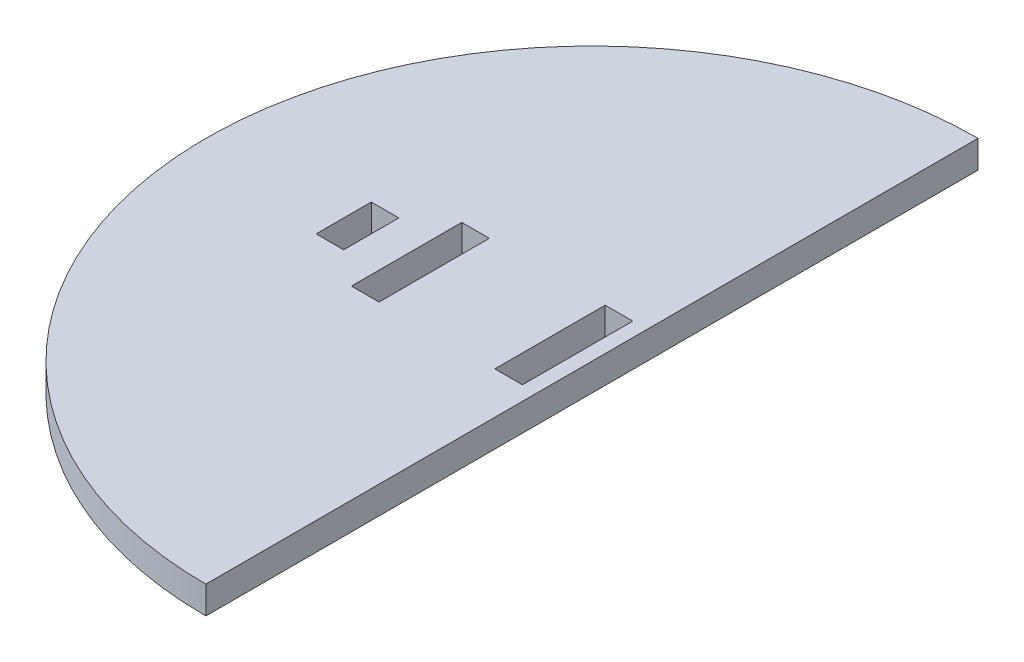
SolidWorks part; units mm, degrees
ref_plane "Front Plane" through (0, 0, 0) normal (0, 0, 1) x (1, 0, 0)
ref_plane "Top Plane" through (0, 0, 0) normal (0, 1, 0) x (1, 0, 0)
ref_plane "Right Plane" through (0, 0, 0) normal (1, 0, 0) x (0, 0, -1)
sketch "Sketch1" plane through (0, 0, 0) normal (0, 1, 0) x (1, 0, 0)
  line L0 (0, 70) -> (0, -70)
  line L2 (-45, -5) -> (-40, -5)
  line L3 (-45, -5) -> (-45, 5)
  line L4 (-45, 5) -> (-40, 5)
  line L5 (-40, -5) -> (-40, 5)
  line L6 (-45, -5) -> (-40, 5) construction
  line L7 (-45, 5) -> (-40, -5) construction
  arc A0 (0, 70) -> (0, -70) centre (0, 0) ccw
  point P4 (-42.5, 0)
  dimension "D1" = 70
  dimension "D5" = 140
  dimension "D2" = 10
  dimension "D3" = 5
  dimension "D4" = 40
extrude "Boss-Extrude1" add sketch "Sketch1" along normal blind 5 contours L0 A0 | L3 L2 L5 L4
sketch "Sketch2" plane through (0, 5, 0) normal (0, 1, 0) x (1, 0, 0)
  line L7 (0, 0) -> (-2.6, 0)
  line L8 (0, 70) -> (0, -70) construction
  line L9 (-2.6, 0) -> (-2.6, 10)
  line L10 (-2.6, 10) -> (-7.6, 10)
  line L11 (-7.6, 10) -> (-7.6, -10)
  line L12 (-7.6, -10) -> (-2.6, -10)
  line L13 (-2.6, -10) -> (-2.6, 0)
  dimension "D1" = 5
  dimension "D2" = 20
  dimension "D3" = 2.6
  dimension "D4" = 10
extrude "Cut-Extrude1" cut sketch "Sketch2" against normal blind 10 contours L12 L13 L9 L10 L11
sketch "Sketch3" plane through (0, 5, 0) normal (0, 1, 0) x (1, 0, 0)
  line L0 (0, 0) -> (-28.6, 0)
  line L1 (0, 70) -> (0, -70) construction
  line L2 (-28.6, 0) -> (-28.6, 10)
  line L3 (-28.6, 10) -> (-33.6, 10)
  line L4 (-33.6, 10) -> (-33.6, -10)
  line L5 (-33.6, -10) -> (-28.6, -10)
  line L6 (-28.6, 0) -> (-28.6, -10)
  dimension "D1" = 28.6
  dimension "D2" = 5
  dimension "D3" = 20
  dimension "D4" = 10
extrude "Cut-Extrude2" cut sketch "Sketch3" against normal blind 10 contours L6 L2 L3 L4 L5
